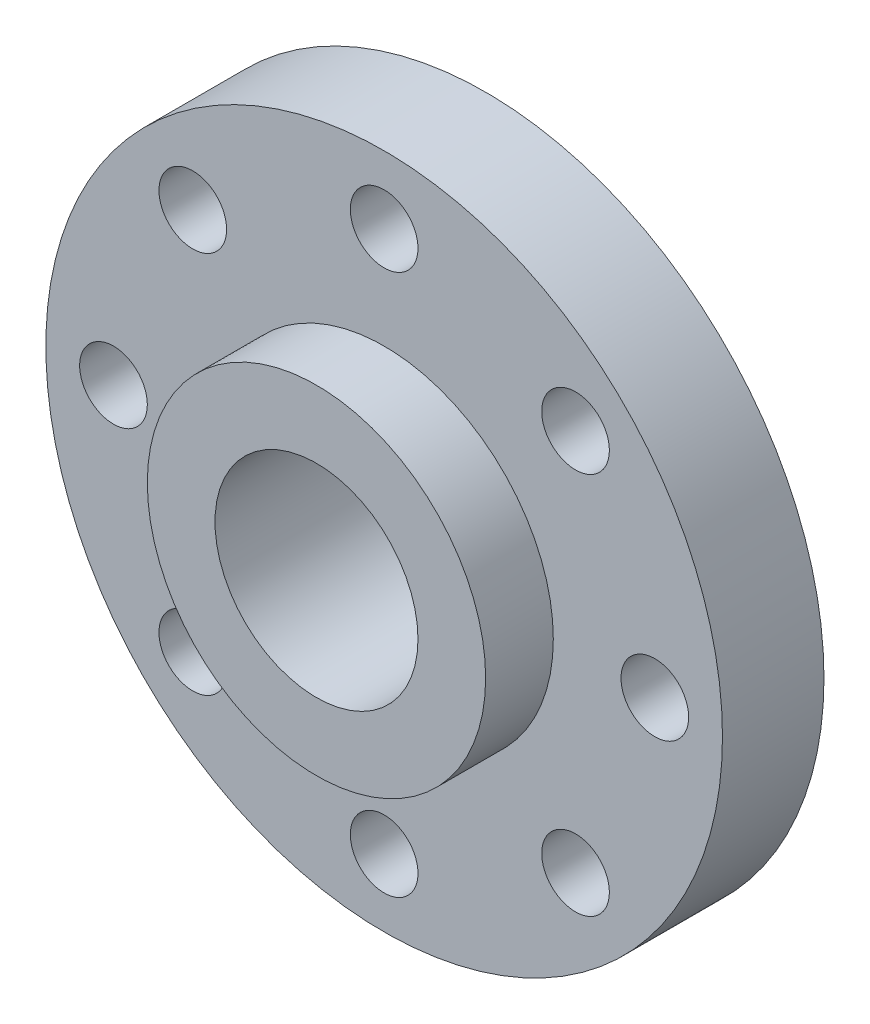
SolidWorks part; units mm, degrees
ref_plane "前视基准面" through (0, 0, 0) normal (0, 0, 1) x (1, 0, 0)
ref_plane "上视基准面" through (0, 0, 0) normal (0, 1, 0) x (1, 0, 0)
ref_plane "右视基准面" through (0, 0, 0) normal (1, 0, 0) x (0, 0, -1)
other "Configuration Table"
sketch "草图1" plane through (0, 0, 0) normal (0, 0, 1) x (1, 0, 0)
  circle A0 centre (0, 0) radius 10
  dimension "D1" = 20
extrude "凸台-拉伸1" add sketch "草图1" along normal blind 3 contours A0
sketch "草图2" plane through (0, 0, 3) normal (0, 0, 1) x (1, 0, 0)
  circle A0 centre (0, 0) radius 5
  dimension "D1" = 10
extrude "凸台-拉伸2" add sketch "草图2" along normal blind 2
sketch "草图3" plane through (0, 0, 3) normal (0, 0, 1) x (1, 0, 0)
  line L0 (0, 10) -> (0, 8)
  circle A0 centre (0, 0) radius 10 construction
  circle A1 centre (0, 8) radius 1
  circle A2 centre (5.6569, 5.6569) radius 1
  circle A3 centre (8, 0) radius 1
  circle A4 centre (5.6569, -5.6569) radius 1
  circle A5 centre (0, -8) radius 1
  circle A6 centre (-5.6569, -5.6569) radius 1
  circle A7 centre (-8, 0) radius 1
  circle A8 centre (-5.6569, 5.6569) radius 1
  point P23 (0, 0)
  dimension "D1" = 2
  dimension "D2" = 8
extrude "切除-拉伸1" cut sketch "草图3" against normal through all
sketch "草图4" plane through (0, 0, 5) normal (0, 0, 1) x (1, 0, 0)
  circle A0 centre (0, 0) radius 3
  dimension "D1" = 6
extrude "切除-拉伸2" cut sketch "草图4" against normal through all contours A0
